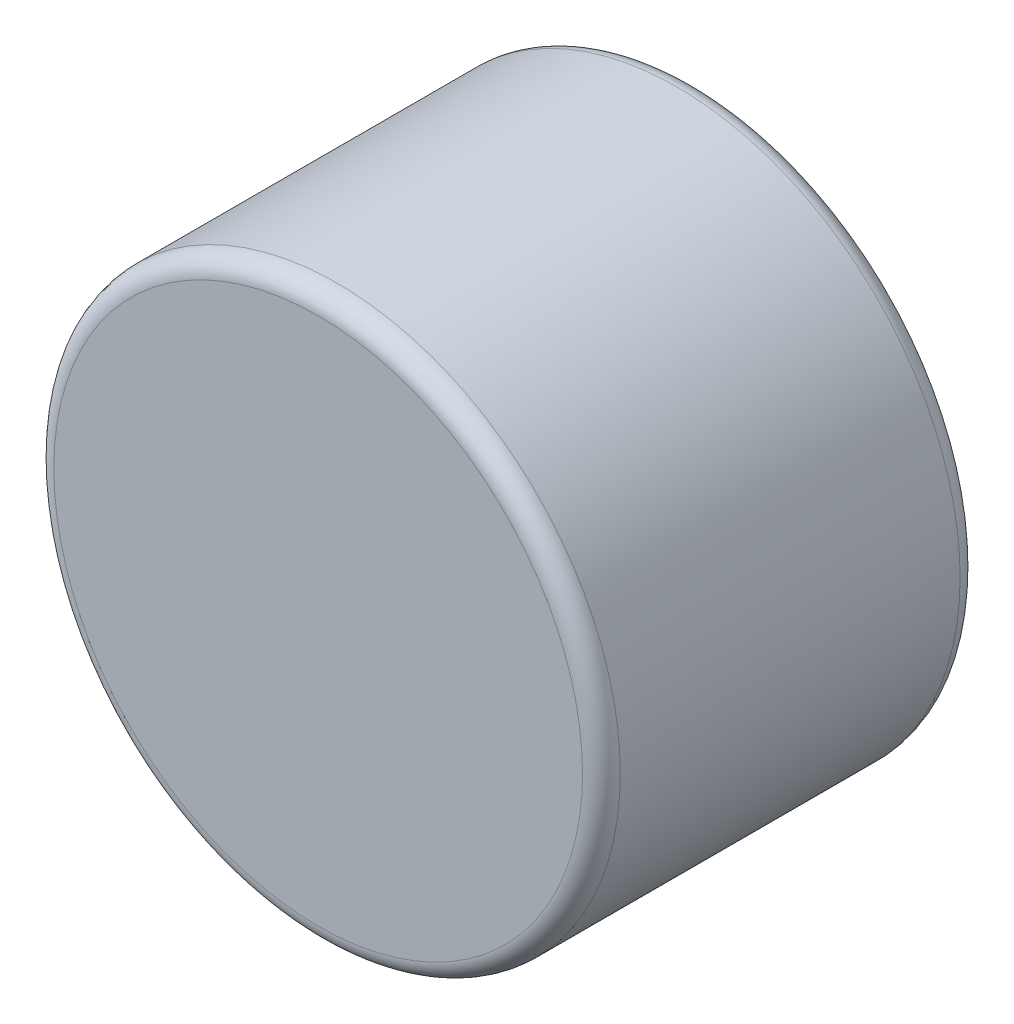
SolidWorks part; units mm, degrees
ref_plane "前视基准面" through (0, 0, 0) normal (0, 0, 1) x (1, 0, 0)
ref_plane "上视基准面" through (0, 0, 0) normal (0, 1, 0) x (1, 0, 0)
ref_plane "右视基准面" through (0, 0, 0) normal (1, 0, 0) x (0, 0, -1)
sketch "草图1" plane through (0, 0, 0) normal (0, 0, 1) x (1, 0, 0)
  circle A0 centre (0, 0) radius 3
  dimension "D1" = 6
extrude "凸台-拉伸1" add sketch "草图1" along normal blind 4
fillet "圆角1" radius 0.2 2 edges at (3, 0, 4) (3, 0, 0)
